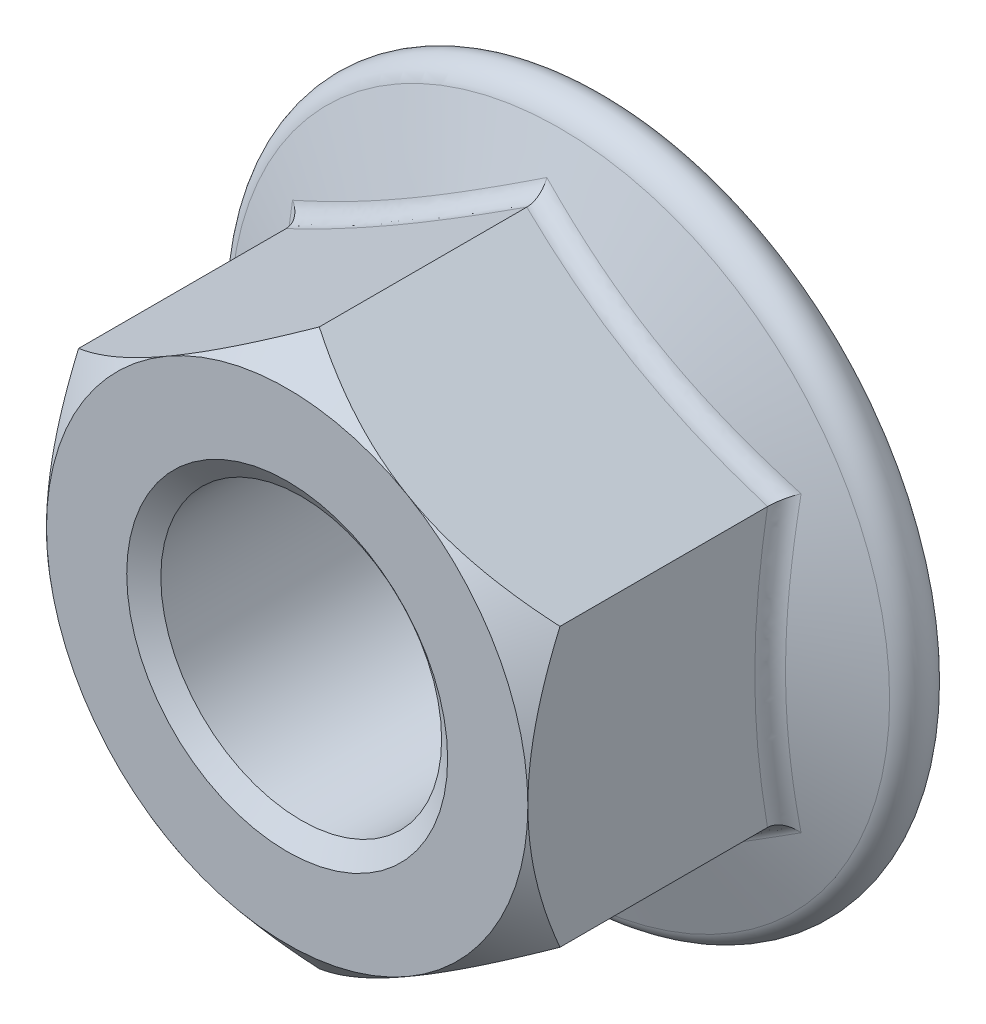
SolidWorks part; units mm, degrees
ref_plane "Plane1" through (0, 0, 0) normal (0, 0, 1) x (1, 0, 0)
ref_plane "Plane2" through (0, 0, 0) normal (0, 1, 0) x (1, 0, 0)
ref_plane "Plane3" through (0, 0, 0) normal (1, 0, 0) x (0, 0, -1)
sketch "BaseNutSke" plane through (0, 0, 0) normal (0, 0, 1) x (1, 0, 0)
  line L6 (12, 6.9282) -> (12, -6.9282)
  line L7 (-12, 6.9282) -> (-12, -6.9282)
  line L8 (12, 6.9282) -> (0, 13.8564)
  line L9 (0, 13.8564) -> (-12, 6.9282)
  line L10 (-12, -6.9282) -> (0, -13.8564)
  line L11 (0, -13.8564) -> (12, -6.9282)
  circle A0 centre (0, 0) radius 7
  dimension "D4" = 12
  dimension "Tap_drill" = 14
  dimension "D1" = 120
  dimension "D2" = 12
  dimension "D3" = 12
  dimension "Width_flats" = 24
extrude "BaseNut" add sketch "BaseNutSke" against normal blind 16
cosmetic thread "ThreadCosmetic" [suppressed] parameters "Thread_major"=16
sketch "Sketch6" plane through (0, 0, 0) normal (1, 0, 0) x (0, 0, -1)
  line L0 (10.1656, 7) -> (13.6, 16.4359)
  line L1 (16, 7) -> (16, 16.0127)
  line L2 (13.6, 32.2909) -> (13.6, 16.4359) construction
  line L3 (23.7075, 17.25) -> (19.5103, 17.25) construction
  line L4 (16, 7) -> (10.1656, 7)
  line L5 (23.7075, -17.25) -> (19.5103, -17.25) construction
  line L6 (16, 6.9282) -> (16, 13.8564) construction
  line L7 (0, 0) -> (32.9582, 0) construction
  line L8 (16, -7) -> (10.1656, -7) construction
  line L9 (16, 0) -> (0, 0) construction
  arc A0 (16, 16.0127) -> (13.6, 16.4359) centre (14.7627, 16.0127) ccw
  dimension "D1" = 14
  dimension "D2" = 20
  dimension "Flange_dia" = 34.5
  dimension "Flange_thickness" = 2.4
revolve "Flange" add sketch "Sketch6" angle 360 about L7
sketch "Sketch3" plane through (0, 0, 0) normal (1, 0, 0) x (0, 0, -1)
  line L0 (16, 12) -> (14.4, 13.8564) construction
  line L1 (14.4, 13.8564) -> (14.4, 26.5564) construction
  line L2 (14.4, 26.5564) -> (28.7, 26.5564) construction
  line L3 (28.7, 26.5564) -> (28.7, 12) construction
  line L4 (28.7, 12) -> (16, 12) construction
  line L5 (16, 6.9282) -> (16, 13.8564) construction
  line L6 (12.6612, 13.8564) -> (0, 13.8564) construction
  line L7 (0, 0) -> (38.6776, 0) construction
  line L8 (16, 0) -> (0, 0) construction
  line L9 (8, 13.8564) -> (8, 44.222) construction
  line L10 (1.6, 26.5564) -> (-12.7, 26.5564)
  line L11 (-12.7, 26.5564) -> (-12.7, 12)
  line L12 (-12.7, 12) -> (0, 12)
  line L13 (0, 12) -> (1.6, 13.8564)
  line L14 (1.6, 13.8564) -> (1.6, 26.5564)
  line L16 (12.6612, 13.8564) -> (0, 13.8564) construction
  dimension "D1" = 12
  dimension "D2" = 1.6
  dimension "D3" = 12.7
  dimension "D4" = 12.7
  dimension "D5" = 8
revolve "Double-Chamfer" cut sketch "Sketch3" angle 360 about L7
fillet "FlangeFillet" radius 0.96 6 edges
sketch "Sketch5"
  line L0 (15.9746, 8) -> (15.2044, 6.9)
  line L1 (16.0254, 8) -> (15.9746, 8)
  line L2 (16.0254, 8) -> (16.0254, 6.9)
  line L3 (16.0254, 6.9) -> (15.2044, 6.9)
  line L6 (-0.0508, 8) -> (0, 8)
  line L7 (0, 8) -> (0.7702, 6.9)
  line L9 (0.7702, 6.9) -> (-0.0508, 6.9)
  line L10 (-0.0508, 6.9) -> (-0.0508, 8)
  line L11 (25.0375, 0) -> (38.388, 0) construction
  line L12 (16, 0) -> (0, 0) construction
  dimension "D1" = 35
  dimension "D2" = 0.0508
  dimension "ThreadMajor" = 8
  dimension "Offset1" = 16.0254
pattern_linear "ThdSchPat" [suppressed]
revolve "ThreadSchematic" [suppressed] cut sketch "ThdSchSke" angle 360 about L6
sketch "ThdSchSke" plane through (0, 0, 0) normal (0, 1, 0) x (1, 0, 0)
  line L0 (-8, 0.0254) -> (-7, 0.7256)
  line L1 (-7, 0.7256) -> (-3.5, 0.7256)
  line L2 (-3.5, 0.7256) -> (-3.5, -0.6748)
  line L3 (-3.5, -0.6748) -> (-7, -0.6748)
  line L4 (-7, -0.6748) -> (-8, 0.0254)
  line L5 (-3.175, 2) -> (3.175, 2) construction
  line L6 (0, 2) -> (0, -2.9874) construction
  line L7 (0, 15.2744) -> (0, 0.7002) construction
  dimension "D1" = 0.0254
  dimension "VeeAngle" = 70
  dimension "SideAngle" = 55
  dimension "OverCut" = 7
  dimension "Tap_Drill" = 14
  dimension "Advance" = 2
  dimension "Thread_major" = 16
revolve "EndChamfer" cut sketch "Sketch5" angle 360 about L11
equation "\"D2@BaseNutSke\" = \"Width_flats@BaseNutSke\" / 2"
equation "\"D3@BaseNutSke\" = \"Width_flats@BaseNutSke\" / 2"
equation "\"D1@Sketch3\" = \"Width_flats@BaseNutSke\" /2"
equation "\"D2@Sketch3\" = \"Thread_major@ThreadCosmetic\" *.1"
equation "\"D4@BaseNutSke\" = \"D3@BaseNutSke\""
equation "\"Thread_major@ThdSchSke\" = \"Thread_major@ThreadCosmetic\""
equation "\"Tap_drill@ThdSchSke\" = \"Tap_drill@BaseNutSke\""
equation "\"Overcut@ThdSchSke\" = \"Tap_drill@ThdSchSke\" * 0.5"
equation "\"Num_threads@ThdSchPat\" = int(  ( \"Thickness@BaseNut\" - 0.0508 ) / \"Advance@ThdSchSke\" + 0.999 )  + 1"
equation "\"Advance@ThdSchPat\" = ( \"Thickness@BaseNut\" - 0.0508 ) /  (\"Num_threads@ThdSchPat\" - 1) 'relax it"
equation "' \"Num_threads@ThdSchPat\" = \"Num_threads@ThdSchPat\" - sgn( \"Num_threads@ThdSchPat\" - 1) '---chamfered tips only---"
equation "\"ThreadMajor@Sketch5\" = \"Thread_major@ThreadCosmetic\" * 0.5"
equation "\"ChamferDepth@Sketch5\" = (\"Thread_major@ThreadCosmetic\" - \"Tap_drill@BaseNutSke\") * 0.55"
equation "\"Offset1@Sketch5\" = \"Thickness@BaseNut\" + 0.0254"
equation "\"Offset2@Sketch5\" = \"Offset1@Sketch5\" + 0.0508"
equation "\"D1@Sketch6\" = \"Tap_drill@BaseNutSke\""
equation "\"D5@Sketch3\" = \"Thickness@BaseNut\" / 2"
